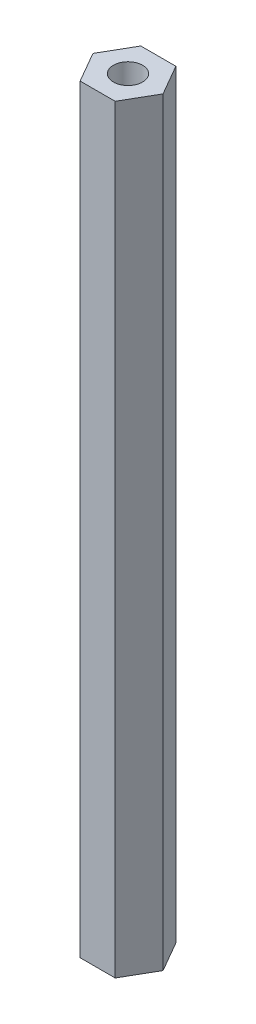
SolidWorks part; units mm, degrees
ref_plane "前视基准面" through (0, 0, 0) normal (0, 0, 1) x (1, 0, 0)
ref_plane "上视基准面" through (0, 0, 0) normal (0, 1, 0) x (1, 0, 0)
ref_plane "右视基准面" through (0, 0, 0) normal (1, 0, 0) x (0, 0, -1)
sketch "草图1" plane through (0, 0, 0) normal (0, 1, 0) x (1, 0, 0)
  line L1 (1.5, 2.5981) -> (-1.5, 2.5981)
  line L2 (-1.5, 2.5981) -> (-3, 0)
  line L3 (-3, 0) -> (-1.5, -2.5981)
  line L4 (-1.5, -2.5981) -> (1.5, -2.5981)
  line L5 (1.5, -2.5981) -> (3, 0)
  line L6 (3, 0) -> (1.5, 2.5981)
  circle A0 centre (0, 0) radius 2.5981 construction
  dimension "D1" = 3
extrude "凸台-拉伸1" add sketch "草图1" along normal blind 65
hole_wizard "M3 螺纹孔1" positions "草图2" profile "草图3" tap size "M3" standard "GB" end condition through all
sketch "草图2" plane through (0, 65, 0) normal (0, 1, 0) x (1, 0, 0)
  point P0 (0, 0)
sketch "草图3" plane through (0, 65, 0) normal (1, 0, 0) x (0, 0, 1)
  line L0 (0, 0) -> (0, 65)
  line L1 (0, 65) -> (1.25, 65)
  line L2 (1.25, 65) -> (1.25, 0)
  line L5 (1.25, 0) -> (0, 0)
  line L11 (0, -6.35) -> (0, 107.95) construction
  dimension "通孔螺纹孔钻头直径" = 2.5
  dimension "通孔螺纹孔钻头深度" = 65
cosmetic thread "孔螺蚊线1" parameters "D2"=3
